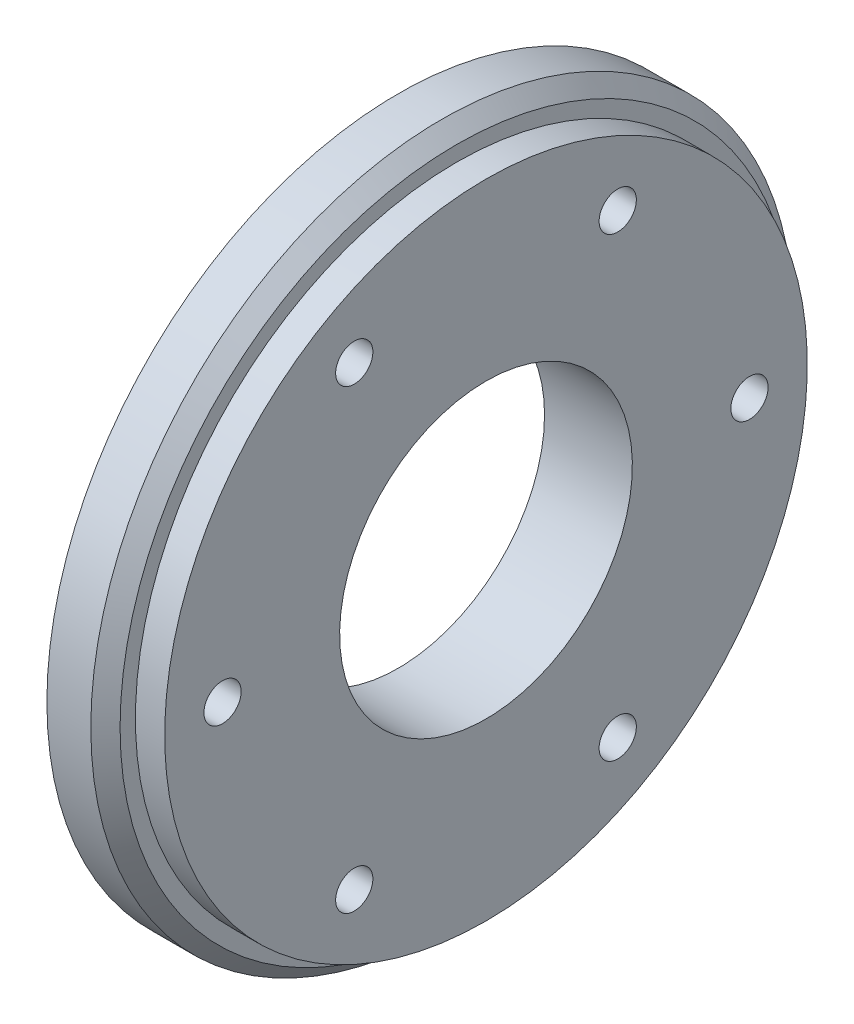
SolidWorks part; units mm, degrees
material "6061-T6 (SS)"
ref_plane "Front Plane" through (0, 0, 0) normal (0, 0, 1) x (1, 0, 0)
ref_plane "Top Plane" through (0, 0, 0) normal (0, 1, 0) x (1, 0, 0)
ref_plane "Right Plane" through (0, 0, 0) normal (1, 0, 0) x (0, 0, -1)
sketch "Sketch1" plane through (0, 0, 0) normal (1, 0, 0) x (0, 0, -1)
  line L1 (28.575, 0) -> (14.2875, 24.7467) construction
  line L2 (14.2875, 24.7467) -> (-14.2875, 24.7467) construction
  line L3 (-14.2875, 24.7467) -> (-28.575, 0) construction
  line L4 (-28.575, 0) -> (-14.2875, -24.7467) construction
  line L5 (-14.2875, -24.7467) -> (14.2875, -24.7467) construction
  line L6 (14.2875, -24.7467) -> (28.575, 0) construction
  circle A0 centre (0, 0) radius 38.1
  circle A1 centre (0, 0) radius 15.875
  circle A2 centre (0, 0) radius 28.575 construction
  circle A3 centre (14.2875, 24.7467) radius 2.0193
  circle A4 centre (28.575, 0) radius 2.0193
  circle A5 centre (14.2875, -24.7467) radius 2.0193
  circle A6 centre (-14.2875, -24.7467) radius 2.0193
  circle A7 centre (-28.575, 0) radius 2.0193
  circle A8 centre (-14.2875, 24.7467) radius 2.0193
  dimension "D1" = 76.2
  dimension "D2" = 31.75
  dimension "D3" = 57.15
  dimension "D4" = 4.0386
extrude "Boss-Extrude1" add sketch "Sketch1" along normal mid plane 6.35
sketch "Sketch2" plane through (3.175, 0, 0) normal (1, 0, 0) x (0, 0, -1)
  circle A0 centre (0, 0) radius 34.8488
  circle A1 centre (0, 0) radius 38.1 construction
  circle A2 centre (0, 0) radius 15.875 construction
  circle A3 centre (-28.575, 0) radius 2.0193 construction
  circle A4 centre (-14.2875, 24.7467) radius 2.0193 construction
  circle A5 centre (14.2875, 24.7467) radius 2.0193 construction
  circle A6 centre (28.575, 0) radius 2.0193 construction
  circle A7 centre (14.2875, -24.7467) radius 2.0193 construction
  circle A8 centre (-14.2875, -24.7467) radius 2.0193 construction
  circle A9 centre (0, 0) radius 15.875
  circle A10 centre (-28.575, 0) radius 2.0193
  circle A11 centre (-14.2875, 24.7467) radius 2.0193
  circle A12 centre (14.2875, 24.7467) radius 2.0193
  circle A13 centre (28.575, 0) radius 2.0193
  circle A14 centre (14.2875, -24.7467) radius 2.0193
  circle A15 centre (-14.2875, -24.7467) radius 2.0193
  dimension "D1" = 3.2512
extrude "Boss-Extrude2" add sketch "Sketch2" along normal blind 3.175
chamfer "Chamfer1" distance 1.5875 angle 45 1 edges at (3.175, 0, -38.1)
